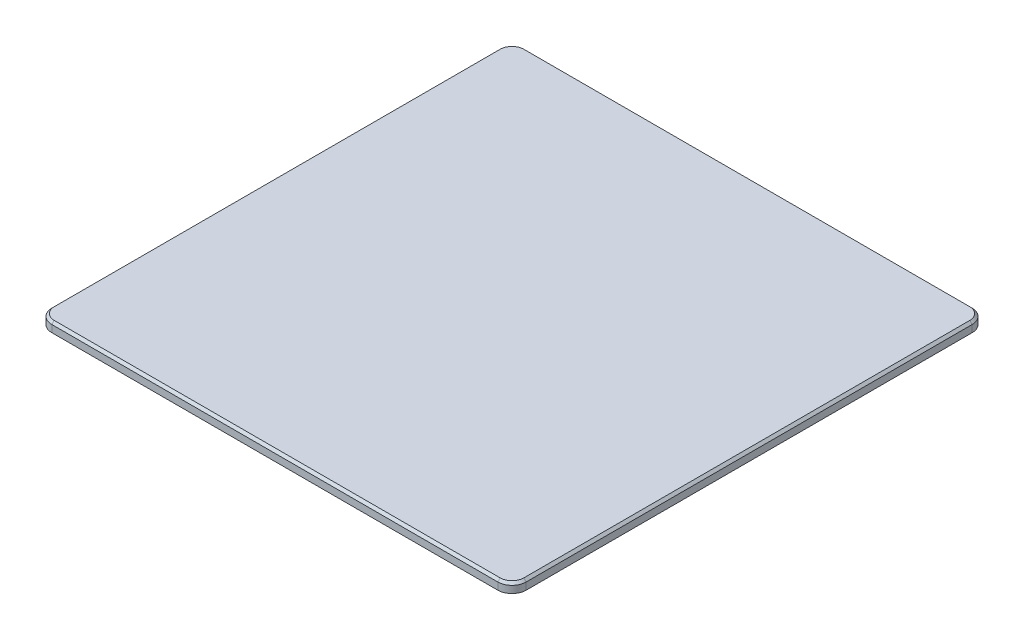
SolidWorks part; units mm, degrees
ref_plane "Front Plane" through (0, 0, 0) normal (0, 0, 1) x (1, 0, 0)
ref_plane "Top Plane" through (0, 0, 0) normal (0, 1, 0) x (1, 0, 0)
ref_plane "Right Plane" through (0, 0, 0) normal (1, 0, 0) x (0, 0, -1)
sketch "草图1" plane through (0, 0, 0) normal (0, 1, 0) x (1, 0, 0)
  line L1 (-47, 50) -> (47, 50)
  line L2 (-50, 47) -> (-50, -47)
  line L3 (-47, -50) -> (47, -50)
  line L4 (50, 47) -> (50, -47)
  line L5 (-50, 50) -> (50, -50) construction
  line L6 (-50, -50) -> (50, 50) construction
  arc A0 (47, 50) -> (50, 47) centre (47, 47) cw
  arc A1 (-50, -47) -> (-47, -50) centre (-47, -47) ccw
  arc A2 (-47, 50) -> (-50, 47) centre (-47, 47) ccw
  arc A3 (47, -50) -> (50, -47) centre (47, -47) ccw
  point P0 (0, 0)
  dimension "D2" = 3
  dimension "D1" = 100
extrude "凸台-拉伸1" add sketch "草图1" along normal blind 2
chamfer "倒角1" distance 0.5 angle 45 8 edges at (50, 2, 0) (49.1213, 2, 49.1213) (0, 2, 50) (-49.1213, 2, 49.1213) (-50, 2, 0) (-49.1213, 2, -49.1213) (0, 2, -50) (49.1213, 2, -49.1213)
